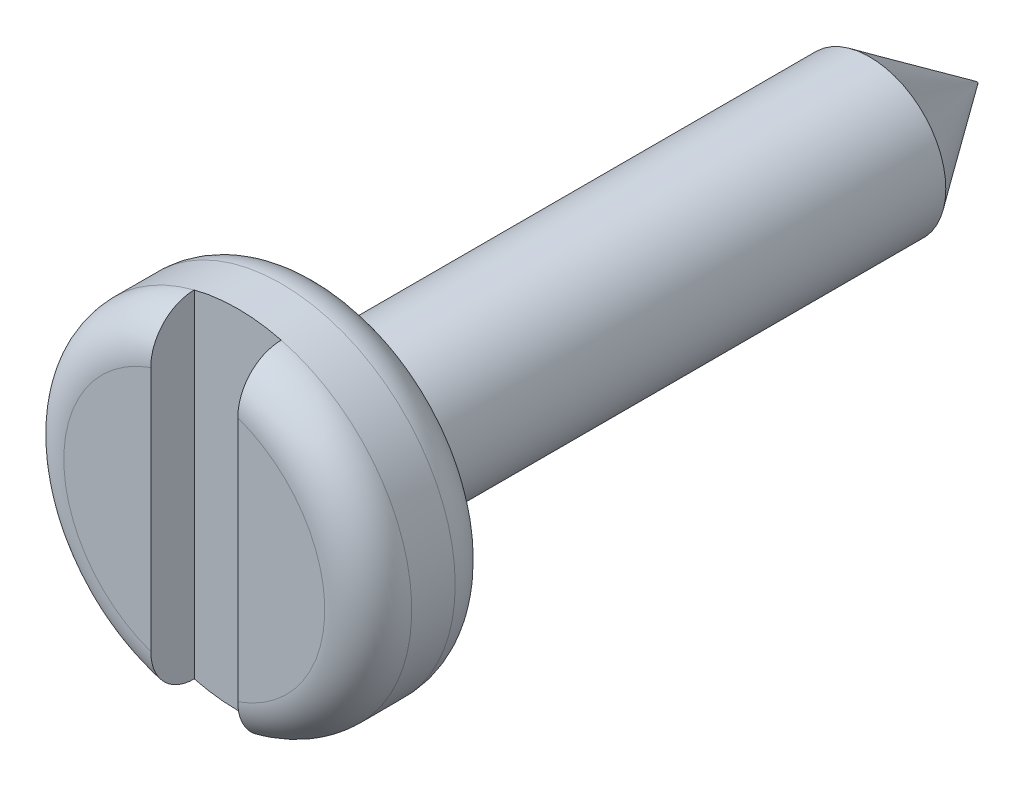
SolidWorks part; units mm, degrees
material "Acero al carbono no aleado"
ref_plane "Alzado" through (0, 0, 0) normal (0, 0, 1) x (1, 0, 0)
ref_plane "Planta" through (0, 0, 0) normal (0, 1, 0) x (1, 0, 0)
ref_plane "Vista lateral" through (0, 0, 0) normal (1, 0, 0) x (0, 0, -1)
sketch "Croquis1" plane through (0, 0, 0) normal (0, 0, 1) x (1, 0, 0)
  circle A0 centre (0, 0) radius 4
  dimension "D1" = 8
extrude "Saliente-Extruir1" add sketch "Croquis1" along normal blind 3
fillet "Redondeo1" radius 1 2 edges at (4, 0, 0) (4, 0, 3)
sketch "Croquis2" plane through (0, 0, 3) normal (0, 0, 1) x (1, 0, 0)
  line L1 (-1, -5.2578) -> (1, -5.2578)
  line L2 (-1, -5.2578) -> (-1, 5.2578)
  line L3 (-1, 5.2578) -> (1, 5.2578)
  line L4 (1, -5.2578) -> (1, 5.2578)
  line L5 (-1, -5.2578) -> (1, 5.2578) construction
  line L6 (-1, 5.2578) -> (1, -5.2578) construction
  point P0 (0, 0)
  dimension "D1" = 2
extrude "Cortar-Extruir1" cut sketch "Croquis2" against normal blind 1
sketch "Croquis3" plane through (0, 0, 0) normal (0, 0, -1) x (-1, 0, 0)
  circle A0 centre (0, 0) radius 1.75
  dimension "D1" = 3.5
extrude "Saliente-Extruir2" add sketch "Croquis3" along normal blind 15
chamfer "Chaflán1" distance 2.47 angle 35 1 edges at (-1.75, 0, -15)
